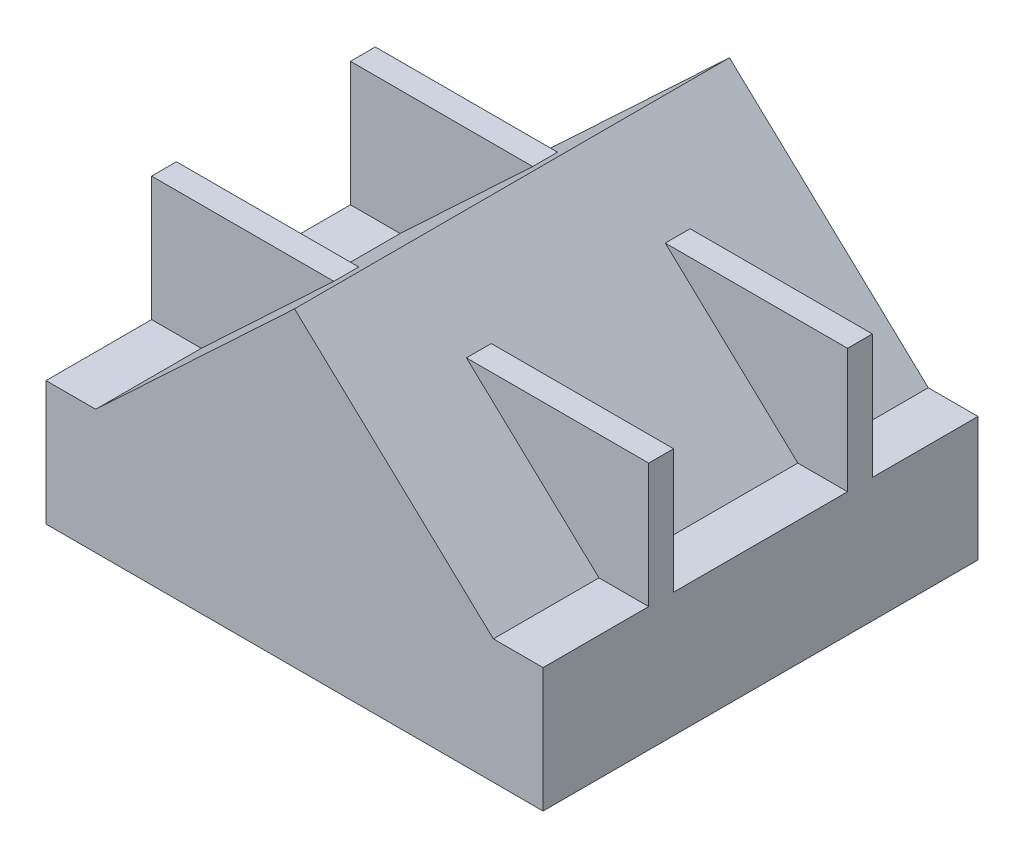
SolidWorks part; units mm, degrees
ref_plane "Front Plane" through (0, 0, 0) normal (0, 0, 1) x (1, 0, 0)
ref_plane "Top Plane" through (0, 0, 0) normal (0, 1, 0) x (1, 0, 0)
ref_plane "Right Plane" through (0, 0, 0) normal (1, 0, 0) x (0, 0, -1)
sketch "Sketch1" plane through (0, 0, 0) normal (0, 1, 0) x (1, 0, 0)
  line L1 (-100, 102.1086) -> (100, 102.1086)
  line L2 (-100, 102.1086) -> (-100, -72.8914)
  line L3 (-100, -72.8914) -> (100, -72.8914)
  line L4 (100, 102.1086) -> (100, -72.8914)
  line L5 (-100, 102.1086) -> (100, -72.8914) construction
  line L6 (-100, -72.8914) -> (100, 102.1086) construction
  point P0 (0, 14.6086)
  dimension "D1" = 200
  dimension "D2" = 175
extrude "Boss-Extrude1" add sketch "Sketch1" along normal blind 50
sketch "Sketch3" plane through (0, 0, 72.8914) normal (0, 0, 1) x (1, 0, 0)
  line L0 (0, 0) -> (0, 125) construction
  line L1 (-80, 64.0087) -> (-80, 32.5887) construction
  line L2 (-100, 50) -> (-100, 0) construction
  line L3 (80, 67.204) -> (80, 29.3935) construction
  line L4 (100, 50) -> (100, 0) construction
  line L5 (-80, 50) -> (0, 125)
  line L6 (-100, 50) -> (100, 50) construction
  line L7 (0, 125) -> (80, 50)
  line L8 (80, 50) -> (-80, 50)
  dimension "D1" = 125
  dimension "D2" = 20
  dimension "D3" = 20
extrude "Boss-Extrude2" add sketch "Sketch3" against normal blind 175
sketch "Sketch4" plane through (0, 50, 0) normal (0, 1, 0) x (1, 0, 0)
  line L0 (-100, 14.6086) -> (100, 14.6086) construction
  line L1 (-100, 102.1086) -> (-100, -72.8914) construction
  line L2 (100, -72.8914) -> (100, 102.1086) construction
  line L4 (-100, 49.6086) -> (100, 49.6086)
  line L5 (-100, 49.6086) -> (-100, 59.6086)
  line L6 (-100, 59.6086) -> (100, 59.6086)
  line L7 (100, 49.6086) -> (100, 59.6086)
  dimension "D1" = 35
  dimension "D2" = 90
  dimension "D3" = 10
extrude "Boss-Extrude3" add sketch "Sketch4" along normal blind 50
sketch "Sketch6" plane through (0, 50, 0) normal (0, 1, 0) x (1, 0, 0)
  line L0 (-100, -30.3914) -> (100, -30.3914) construction
  line L1 (-100, 49.6086) -> (-100, -72.8914) construction
  line L2 (100, -72.8914) -> (100, 49.6086) construction
  line L3 (-100, -72.8914) -> (-80, -72.8914) construction
  line L5 (-100, -30.3914) -> (100, -30.3914)
  line L6 (-100, -30.3914) -> (-100, -20.3914)
  line L7 (-100, -20.3914) -> (100, -20.3914)
  line L8 (100, -30.3914) -> (100, -20.3914)
  dimension "D1" = 42.5
  dimension "D2" = 10
extrude "Boss-Extrude4" add sketch "Sketch6" along normal blind 50
